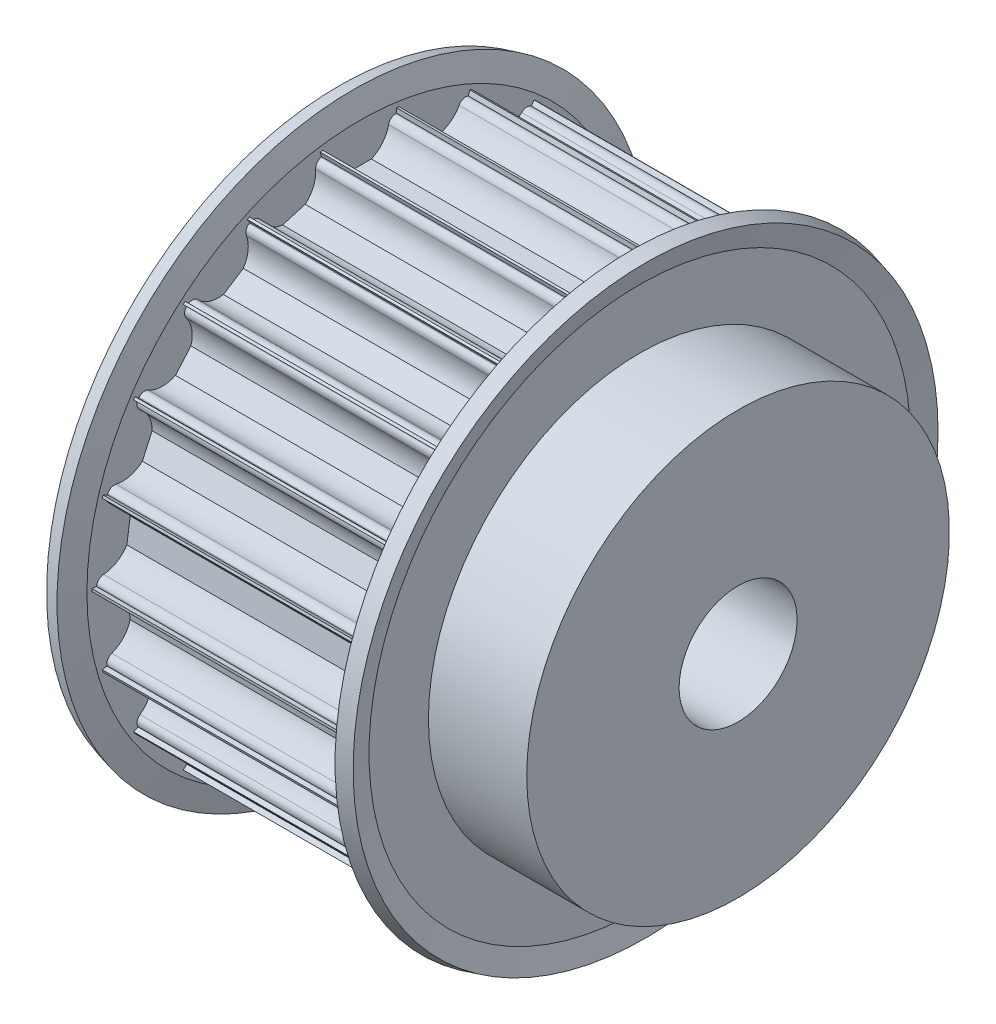
SolidWorks part; units mm, degrees
ref_plane "Front Plane" through (0, 0, 0) normal (0, 0, 1) x (1, 0, 0)
ref_plane "Top Plane" through (0, 0, 0) normal (0, 1, 0) x (1, 0, 0)
ref_plane "Right Plane" through (0, 0, 0) normal (1, 0, 0) x (0, 0, -1)
sketch "Sketch1" plane through (0, 0, 0) normal (0, 0, 1) x (1, 0, 0)
  line L0 (-22.9139, 0) -> (27.5073, 0) construction
  line L1 (0, 6) -> (40, 6)
  line L2 (40, 6) -> (40, 21.5)
  line L3 (40, 21.5) -> (30, 21.5)
  line L4 (30, 21.5) -> (30, 27.25)
  line L5 (30, 27.25) -> (0, 27.25)
  line L6 (0, 27.25) -> (0, 6)
  point P10 (20, 6)
  dimension "D1" = 12
  dimension "D2" = 15.5
  dimension "D3" = 10
  dimension "D4" = 30
  dimension "D5" = 21.25
revolve "Revolve1" add sketch "Sketch1" angle 360 about L0
sketch "Sketch2" plane through (0, 0, 0) normal (-1, 0, 0) x (0, 0, 1)
  line L0 (3.6742, 26.5) -> (3.75, 26.5)
  line L1 (-3.75, 28.5) -> (3.75, 28.5)
  line L2 (-3.75, 28.5) -> (-3.75, 26.5)
  line L3 (-3.75, 26.5) -> (-3.6742, 26.5)
  line L4 (3.75, 28.5) -> (3.75, 26.5)
  line L5 (-1.199, 23.75) -> (1.199, 23.75)
  line L6 (0, 29.8133) -> (0, 24.9397) construction
  arc A0 (2.9394, 25.9) -> (1.199, 23.75) centre (0, 26.5) cw
  arc A1 (-1.199, 23.75) -> (-2.9394, 25.9) centre (0, 26.5) cw
  arc A2 (2.9394, 25.9) -> (3.6742, 26.5) centre (3.6742, 25.75) cw
  arc A3 (-2.9394, 25.9) -> (-3.6742, 26.5) centre (-3.6742, 25.75) ccw
  point P3 (0, 26.5)
  point P10 (3, 26.5)
  point P14 (-3, 26.5)
  dimension "D3" = 3
  dimension "D6" = 0.75
  dimension "D1" = 2
  dimension "D2" = 7.5
  dimension "D4" = 26.5
  dimension "D5" = 2.75
extrude "Cut-Extrude1" cut sketch "Sketch2" against normal up to next
pattern_circular "CirPattern1" count 22 over 360 about axis through (0, 0, 0) along (1, 0, 0) of "Cut-Extrude1"
sketch "Sketch3" plane through (0, 0, 0) normal (0, 0, 1) x (1, 0, 0)
  line L0 (1.5, 27.7407) -> (0.0511, 27.3525) construction
  line L1 (0, 27.7407) -> (1.5, 27.7407) construction
  line L2 (0, 27.7407) -> (0, 22.7407)
  line L3 (0, 22.7407) -> (1.5, 22.7407)
  line L4 (1.5, 27.7407) -> (1.5, 22.7407)
  line L5 (1.5, 27.7407) -> (0.8569, 30.1407)
  line L6 (0.0511, 27.3525) -> (-0.592, 29.7525)
  line L7 (0.8569, 30.1407) -> (-0.592, 29.7525)
  line L8 (0, 26.9907) -> (30, 26.9907) construction
  line L9 (0, 26.4617) -> (0, 25.679) construction
  line L10 (15, 26.9539) -> (15, -28.3327) construction
  line L11 (30, 26.9539) -> (0, 26.9539) construction
  line L12 (30, 27.7407) -> (28.5, 27.7407) construction
  line L13 (28.5, 27.7407) -> (29.9489, 27.3525) construction
  line L14 (29.1431, 30.1407) -> (30.592, 29.7525)
  line L15 (29.9489, 27.3525) -> (30.592, 29.7525)
  line L16 (28.5, 27.7407) -> (29.1431, 30.1407)
  line L17 (28.5, 27.7407) -> (28.5, 22.7407)
  line L18 (30, 22.7407) -> (28.5, 22.7407)
  line L19 (30, 27.7407) -> (30, 22.7407)
  dimension "D1" = 1.5
  dimension "D2" = 5
  dimension "D3" = 1.5
  dimension "D4" = 165
  dimension "D5" = 2.4
  dimension "D6" = 0.75
revolve "Revolve2" add sketch "Sketch3" angle 360 about axis through (-22.9139, 0, 0) along (-1, 0, 0)
